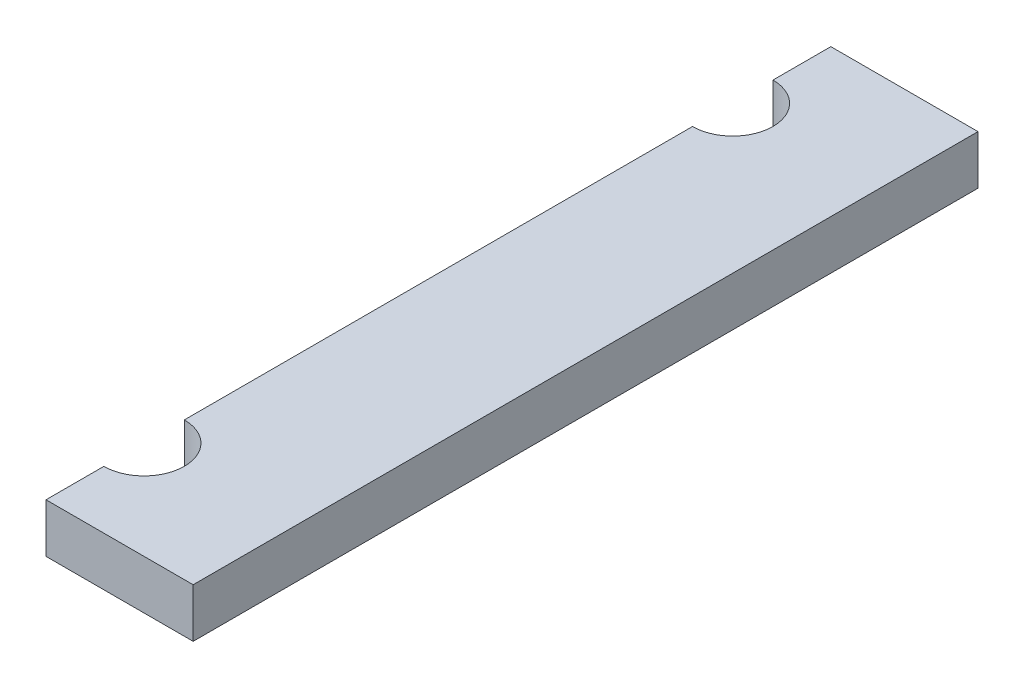
SolidWorks part; units mm, degrees
ref_plane "Front Plane" through (0, 0, 0) normal (0, 0, 1) x (1, 0, 0)
ref_plane "Top Plane" through (0, 0, 0) normal (0, 1, 0) x (1, 0, 0)
ref_plane "Right Plane" through (0, 0, 0) normal (1, 0, 0) x (0, 0, -1)
sketch "Sketch1" plane through (0, 0, 0) normal (0, 1, 0) x (1, 0, 0)
  line L0 (0, 40) -> (15, 40) construction
  line L1 (0, 0) -> (15, 0)
  line L2 (0, 0) -> (0, 80)
  line L3 (0, 80) -> (15, 80)
  line L4 (15, 0) -> (15, 80)
  circle A0 centre (0, 70) radius 4.1
  circle A1 centre (0, 10) radius 4.1
  dimension "D4" = 8.2
  dimension "D1" = 80
  dimension "D2" = 15
  dimension "D3" = 60
extrude "Boss-Extrude1" add sketch "Sketch1" along normal blind 5 contours L0 L2 A1 L1 L4 | L2 L0 L4 L3 A0
